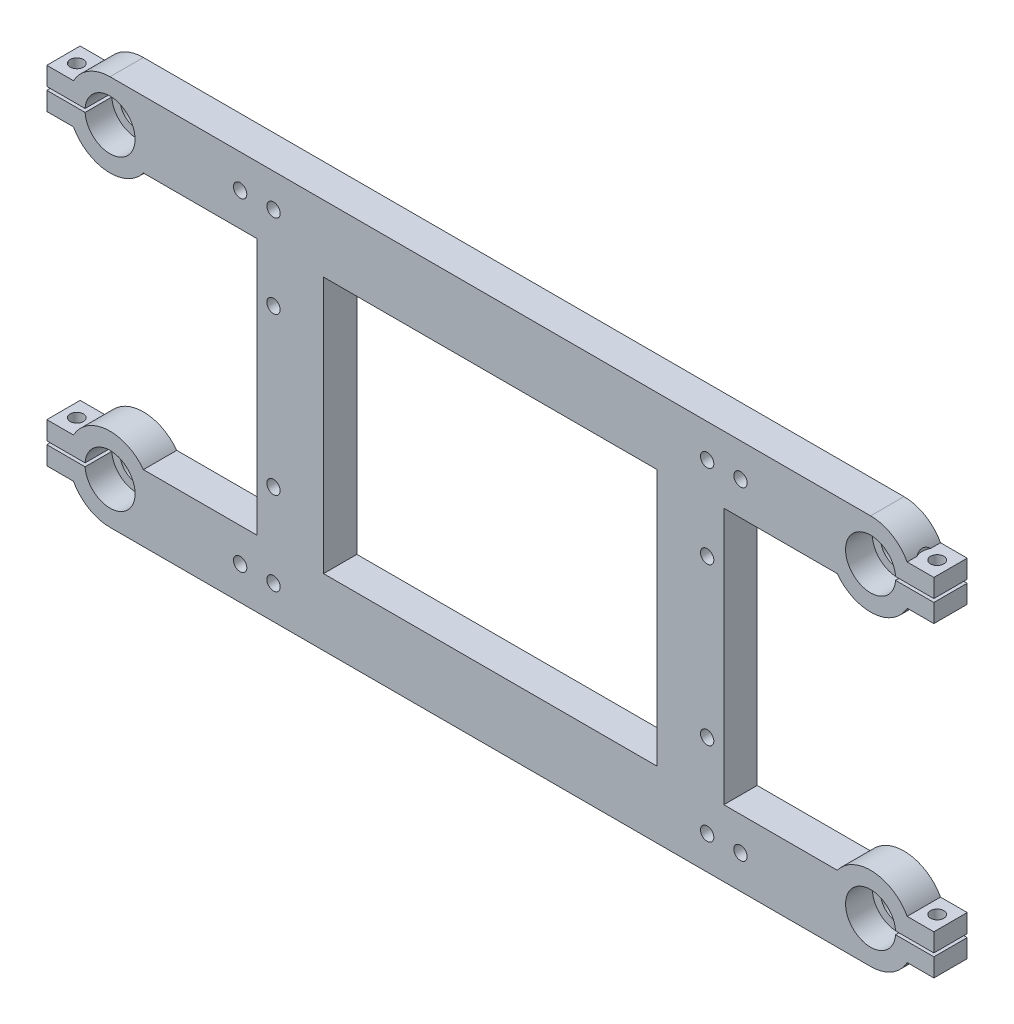
SolidWorks part; units mm, degrees
material "1060 合金"
ref_plane "前视基准面" through (0, 0, 0) normal (0, 0, 1) x (1, 0, 0)
ref_plane "上视基准面" through (0, 0, 0) normal (0, 1, 0) x (1, 0, 0)
ref_plane "右视基准面" through (0, 0, 0) normal (1, 0, 0) x (0, 0, -1)
sketch "草图1" plane through (0, 0, 0) normal (0, 0, 1) x (1, 0, 0)
  line L0 (-104, 84.5) -> (-70, 84.5)
  line L1 (-70, 84.5) -> (-70, 7.5)
  line L2 (-104, 7.5) -> (-70, 7.5)
  line L3 (-114, 104.5) -> (-64, 104.5)
  line L7 (114, -12.5) -> (-114, -12.5)
  line L8 (0, 151.6854) -> (0, -40.7139) construction
  line L9 (-64, 104.5) -> (64, 104.5)
  line L10 (-50, 84.5) -> (50, 84.5)
  line L11 (-50, 84.5) -> (-50, 7.5)
  line L12 (-50, 7.5) -> (50, 7.5)
  line L16 (50, 84.5) -> (50, 7.5)
  line L23 (114, 104.5) -> (64, 104.5)
  line L24 (104, 7.5) -> (70, 7.5)
  line L25 (70, 84.5) -> (70, 7.5)
  line L26 (104, 84.5) -> (70, 84.5)
  circle A0 centre (-114, 0) radius 5
  circle A1 centre (-114, 92) radius 5
  arc A2 (-114, 104.5) -> (-104, 84.5) centre (-114, 92) ccw
  arc A3 (-104, 7.5) -> (-114, -12.5) centre (-114, 0) ccw
  arc A8 (104, 7.5) -> (114, -12.5) centre (114, 0) cw
  arc A9 (114, 104.5) -> (104, 84.5) centre (114, 92) cw
  circle A10 centre (114, 92) radius 5
  circle A11 centre (114, 0) radius 5
  point P5 (0, -12.5)
  point P31 (0, 83.8883)
  point P32 (0, 103.8883)
  point P37 (0, 7.5)
  point P38 (0, 84.5)
  point P39 (0, 104.5)
  dimension "D1" = 10
  dimension "D3" = 25
  dimension "D2" = 92
  dimension "D4" = 50
  dimension "D5" = 20
  dimension "D6" = 70
  dimension "D7" = 20
  dimension "D8" = 228
  dimension "D9" = 20
extrude "凸台-拉伸1" add sketch "草图1" along normal blind 10
sketch "草图3" plane through (0, 0, 10) normal (0, 0, 1) x (1, 0, 0)
  line L0 (0, 111.1634) -> (0, -18.3618) construction
  circle A0 centre (-114, 92) radius 7.5
  circle A1 centre (-114, 0) radius 7.5
  circle A2 centre (-114, 0) radius 5 construction
  circle A3 centre (114, 0) radius 7.5
  circle A4 centre (114, 92) radius 7.5
  dimension "D1" = 15
extrude "切除-拉伸1" cut sketch "草图3" against normal offset from surface (8 mm away) 2 up to face at (109, 92, 0)
sketch "草图5" plane through (0, 0, 0) normal (0, 0, 1) x (1, 0, 0)
  line L0 (0, -12.5) -> (0, 104.5) construction
  line L1 (-114, -12.5) -> (114, -12.5) construction
  line L2 (114, 104.5) -> (-114, 104.5) construction
  line L3 (-70, 84.5) -> (-70, 7.5) construction
  circle A0 centre (-65, 94.5) radius 2
  circle A2 centre (-75, 94.5) radius 2
  circle A3 centre (-65, 69.5) radius 2
  circle A4 centre (-65, 22.5) radius 2
  circle A5 centre (-65, -2.5) radius 2
  circle A6 centre (-75, -2.5) radius 2
  circle A7 centre (75, -2.5) radius 2
  circle A8 centre (65, -2.5) radius 2
  circle A9 centre (65, 22.5) radius 2
  circle A10 centre (65, 69.5) radius 2
  circle A11 centre (75, 94.5) radius 2
  circle A12 centre (65, 94.5) radius 2
  dimension "D1" = 4
  dimension "D2" = 10
  dimension "D3" = 5
  dimension "D4" = 10
  dimension "D5" = 25
  dimension "D6" = 10
  dimension "D7" = 10
  dimension "D8" = 25
extrude "切除-拉伸2" cut sketch "草图5" along normal up to next
sketch "草图6" plane through (0, 0, 10) normal (0, 0, 1) x (1, 0, 0)
  line L0 (0, 104.5) -> (0, -12.5) construction
  line L1 (124.9659, 98) -> (132.9659, 98)
  line L2 (124.9659, 98) -> (124.9659, 86)
  line L3 (124.9659, 86) -> (132.9659, 86)
  line L4 (132.9659, 98) -> (132.9659, 86)
  line L5 (114, 104.5) -> (-114, 104.5) construction
  line L6 (-114, -12.5) -> (114, -12.5) construction
  line L7 (70, 46) -> (-70, 46) construction
  line L8 (70, 7.5) -> (70, 84.5) construction
  line L9 (-70, 84.5) -> (-70, 7.5) construction
  line L10 (132.9659, -6) -> (132.9659, 6)
  line L11 (124.9659, 6) -> (132.9659, 6)
  line L12 (124.9659, -6) -> (124.9659, 6)
  line L13 (124.9659, -6) -> (132.9659, -6)
  line L14 (-124.9659, -6) -> (-132.9659, -6)
  line L15 (-124.9659, -6) -> (-124.9659, 6)
  line L16 (-124.9659, 6) -> (-132.9659, 6)
  line L17 (-132.9659, -6) -> (-132.9659, 6)
  line L18 (-132.9659, 98) -> (-132.9659, 86)
  line L19 (-124.9659, 86) -> (-132.9659, 86)
  line L20 (-124.9659, 98) -> (-124.9659, 86)
  line L21 (-124.9659, 98) -> (-132.9659, 98)
  arc A0 (104, 84.5) -> (114, 104.5) centre (114, 92) ccw construction
  dimension "D1" = 8
  dimension "D2" = 12
extrude "凸台-拉伸2" add sketch "草图6" against normal up to surface (10 mm away) up to face at (-73, -2.5, 0)
sketch "草图7" plane through (0, 0, 10) normal (0, 0, 1) x (1, 0, 0)
  line L0 (0, -12.5) -> (0, 104.5) construction
  line L1 (-114, -12.5) -> (114, -12.5) construction
  line L2 (114, 104.5) -> (-114, 104.5) construction
  line L3 (70, 46) -> (-70, 46) construction
  line L4 (70, 7.5) -> (70, 84.5) construction
  line L5 (-70, 84.5) -> (-70, 7.5) construction
  line L6 (132.9659, 86) -> (132.9659, 98) construction
  line L7 (132.9659, 92.5) -> (117.9659, 92.5)
  line L8 (132.9659, 92.5) -> (132.9659, 91.5)
  line L9 (132.9659, 91.5) -> (117.9659, 91.5)
  line L10 (117.9659, 92.5) -> (117.9659, 91.5)
  line L11 (117.9659, -0.5) -> (117.9659, 0.5)
  line L12 (132.9659, 0.5) -> (117.9659, 0.5)
  line L13 (132.9659, -0.5) -> (132.9659, 0.5)
  line L14 (132.9659, -0.5) -> (117.9659, -0.5)
  line L15 (-132.9659, -0.5) -> (-117.9659, -0.5)
  line L16 (-132.9659, -0.5) -> (-132.9659, 0.5)
  line L17 (-132.9659, 0.5) -> (-117.9659, 0.5)
  line L18 (-117.9659, -0.5) -> (-117.9659, 0.5)
  line L19 (-117.9659, 92.5) -> (-117.9659, 91.5)
  line L20 (-132.9659, 91.5) -> (-117.9659, 91.5)
  line L21 (-132.9659, 92.5) -> (-132.9659, 91.5)
  line L22 (-132.9659, 92.5) -> (-117.9659, 92.5)
  point P20 (132.9659, 92)
  point P21 (132.9659, 92)
  dimension "D1" = 1
  dimension "D2" = 15
extrude "切除-拉伸3" cut sketch "草图7" against normal through all
sketch "草图8" plane through (0, 98, 0) normal (0, 1, 0) x (1, 0, 0)
  line L0 (-132.9659, 0) -> (-132.9659, -10) construction
  line L1 (0, 0) -> (0, -10) construction
  line L2 (114, -10) -> (-114, -10) construction
  circle A0 centre (-128.9659, -5) radius 2
  circle A1 centre (128.9659, -5) radius 2
  point P5 (-132.9659, -5)
  dimension "D1" = 4
  dimension "D2" = 4
extrude "切除-拉伸4" cut sketch "草图8" against normal through all
sketch "草图9" plane through (0, 98, 0) normal (0, 1, 0) x (1, 0, 0)
  line L0 (0, 0) -> (0, -10) construction
  line L1 (114, -10) -> (-114, -10) construction
  circle A0 centre (-128.9659, -5) radius 4.5
  circle A1 centre (128.9659, -5) radius 4.5
  dimension "D1" = 9
extrude "切除-拉伸5" cut sketch "草图9" along normal blind 10
chamfer "倒角1" distance 2 angle 45 12 edges at (-73, 94.5, 0) (-63, 94.5, 0) (-63, 69.5, 0) (-63, 22.5, 0) (-73, -2.5, 0) (-63, -2.5, 0) (63, -2.5, 0) (73, -2.5, 0) (63, 22.5, 0) (63, 69.5, 0) (63, 94.5, 0) (73, 94.5, 0)
